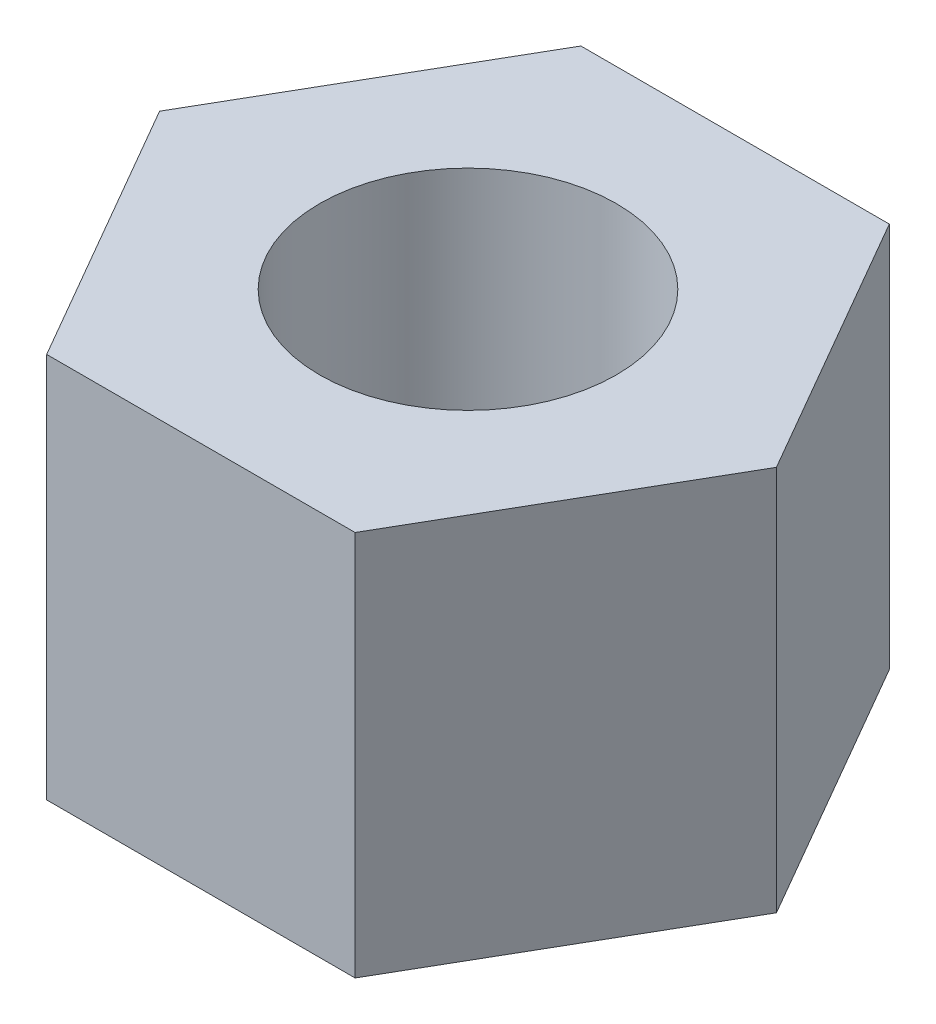
SolidWorks part; units mm, degrees
ref_plane "Alzado" through (0, 0, 0) normal (0, 0, 1) x (1, 0, 0)
ref_plane "Planta" through (0, 0, 0) normal (0, 1, 0) x (1, 0, 0)
ref_plane "Vista lateral" through (0, 0, 0) normal (1, 0, 0) x (0, 0, -1)
sketch "Croquis1" plane through (0, 0, 0) normal (0, 1, 0) x (1, 0, 0)
  line L1 (3.1177, 0) -> (1.5588, 2.7)
  line L2 (1.5588, 2.7) -> (-1.5588, 2.7)
  line L3 (-1.5588, 2.7) -> (-3.1177, 0)
  line L4 (-3.1177, 0) -> (-1.5588, -2.7)
  line L5 (-1.5588, -2.7) -> (1.5588, -2.7)
  line L6 (1.5588, -2.7) -> (3.1177, 0)
  circle A0 centre (0, 0) radius 2.7 construction
  circle A1 centre (0, 0) radius 1.5
  dimension "D2" = 3
  dimension "D1" = 5.4
extrude "Saliente-Extruir1" add sketch "Croquis1" along normal blind 3.9
